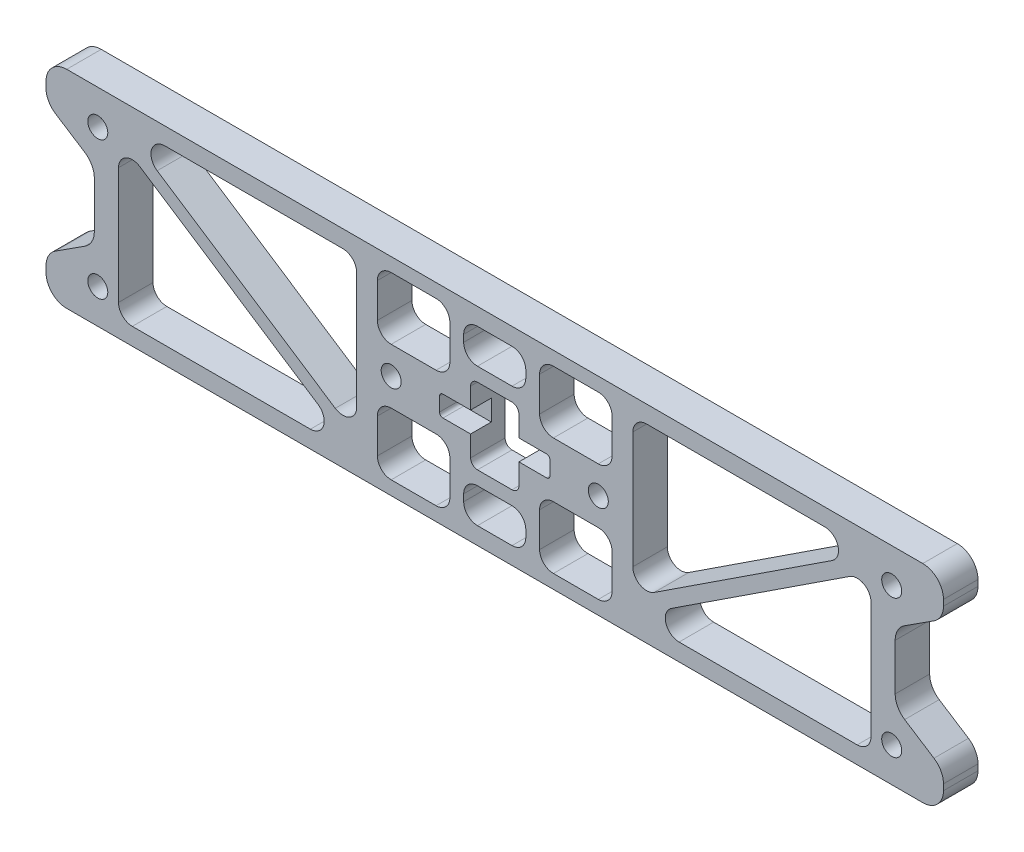
SolidWorks part; units mm, degrees
material "Thornel Mat VMA"
ref_plane "前视基准面" through (0, 0, 0) normal (0, 0, 1) x (1, 0, 0)
ref_plane "上视基准面" through (0, 0, 0) normal (0, 1, 0) x (1, 0, 0)
ref_plane "右视基准面" through (0, 0, 0) normal (1, 0, 0) x (0, 0, -1)
sketch "草图1" plane through (0, 0, 0) normal (0, 0, 1) x (1, 0, 0)
  line L0 (-57.5, 15) -> (-57.5, -15) construction
  line L1 (-65, -15) -> (65, -15)
  line L2 (-65, -15) -> (-65, 15)
  line L3 (-65, 15) -> (65, 15)
  line L4 (65, -15) -> (65, 15)
  line L5 (-65, -15) -> (65, 15) construction
  line L6 (-65, 15) -> (65, -15) construction
  line L7 (57.5, -15) -> (57.5, 15) construction
  line L8 (0, -1000) -> (0, 49000) construction
  line L9 (15, 0) -> (-15, 0) construction
  circle A0 centre (-57.5, -10) radius 1.45
  circle A1 centre (-57.5, 10) radius 1.45
  circle A2 centre (57.5, -10) radius 1.45
  circle A3 centre (57.5, 10) radius 1.45
  circle A4 centre (-15, 0) radius 1.45
  circle A5 centre (15, 0) radius 1.45
  point P0 (0, 0)
  point P23 (0, 0)
  dimension "D5" = 2.9
  dimension "D6" = 20
  dimension "D7" = 5
  dimension "D8" = 2.9
  dimension "D1" = 130
  dimension "D2" = 7.5
  dimension "D3" = 7.5
  dimension "D4" = 30
  dimension "D9" = 30
extrude "凸台-拉伸1" add sketch "草图1" along normal blind 5
sketch "草图3" plane through (0, 0, 5) normal (0, 0, 1) x (1, 0, 0)
  line L1 (-8, -1.5) -> (8, -1.5)
  line L2 (-8, -1.5) -> (-8, 1.5)
  line L3 (-8, 1.5) -> (8, 1.5)
  line L4 (8, -1.5) -> (8, 1.5)
  line L5 (-8, -1.5) -> (8, 1.5) construction
  line L6 (-8, 1.5) -> (8, -1.5) construction
  point P0 (0, 0)
  dimension "D1" = 3
  dimension "D2" = 16
extrude "切除-拉伸1" cut sketch "草图3" against normal blind 3
sketch "草图4" plane through (0, 0, 5) normal (0, 0, 1) x (1, 0, 0)
  line L1 (-3.5, -5.5) -> (3.5, -5.5)
  line L2 (-3.5, -5.5) -> (-3.5, 5.5)
  line L3 (-3.5, 5.5) -> (3.5, 5.5)
  line L4 (3.5, -5.5) -> (3.5, 5.5)
  line L5 (-3.5, -5.5) -> (3.5, 5.5) construction
  line L6 (-3.5, 5.5) -> (3.5, -5.5) construction
  point P0 (0, 0)
  dimension "D1" = 7
  dimension "D2" = 11
extrude "切除-拉伸2" cut sketch "草图4" against normal through all
sketch "草图6" plane through (0, 0, 5) normal (0, 0, 1) x (1, 0, 0)
  line L0 (-65, 9.5) -> (-58, 5)
  line L1 (-65, 15) -> (-65, -15) construction
  line L2 (-58, 5) -> (-58, -5)
  line L3 (-58, -5) -> (-65, -9.5)
  line L4 (-65, -9.5) -> (-65, 9.5)
  line L5 (-54.5, 12.5) -> (-54.5, -12.5)
  line L6 (-54.5, -12.5) -> (-20, -12.5)
  line L7 (-20, -12.5) -> (-20, 12.5)
  line L8 (-20, 12.5) -> (-54.5, 12.5)
  line L9 (-17, 13) -> (-17, 4)
  line L10 (-17, 4) -> (-6.5, 4)
  line L11 (-6.5, 4) -> (-6.5, 13)
  line L12 (-6.5, 13) -> (-17, 13)
  line L13 (65, 15) -> (-65, 15) construction
  line L14 (-65, -15) -> (65, -15) construction
  line L15 (-3.5, 5.5) -> (-3.5, 1.5) construction
  line L16 (0, -1000) -> (0, 49000) construction
  line L17 (-1000, 0) -> (49000, 0) construction
  line L18 (-6.5, -4) -> (-6.5, -13)
  line L19 (-17, -4) -> (-6.5, -4)
  line L20 (-17, -13) -> (-17, -4)
  line L21 (-6.5, -13) -> (-17, -13)
  line L22 (6.5, -13) -> (17, -13)
  line L23 (17, -13) -> (17, -4)
  line L24 (17, -4) -> (6.5, -4)
  line L25 (6.5, -4) -> (6.5, -13)
  line L26 (6.5, 13) -> (17, 13)
  line L27 (6.5, 4) -> (6.5, 13)
  line L28 (17, 4) -> (6.5, 4)
  line L29 (17, 13) -> (17, 4)
  line L30 (20, 12.5) -> (54.5, 12.5)
  line L31 (20, -12.5) -> (20, 12.5)
  line L32 (54.5, -12.5) -> (20, -12.5)
  line L33 (54.5, 12.5) -> (54.5, -12.5)
  line L34 (65, -9.5) -> (65, 9.5)
  line L35 (58, -5) -> (65, -9.5)
  line L36 (58, 5) -> (58, -5)
  line L37 (65, 9.5) -> (58, 5)
  line L38 (3.5, 5.5) -> (-3.5, 5.5) construction
  line L39 (-4.5, 12.5) -> (4.5, 12.5)
  line L40 (-4.5, 12.5) -> (-4.5, 7.5)
  line L41 (-4.5, 7.5) -> (4.5, 7.5)
  line L42 (4.5, 12.5) -> (4.5, 7.5)
  line L43 (-4.5, -7.5) -> (4.5, -7.5)
  line L44 (4.5, -12.5) -> (4.5, -7.5)
  line L45 (-4.5, -12.5) -> (4.5, -12.5)
  line L46 (-4.5, -12.5) -> (-4.5, -7.5)
  circle A0 centre (-57.5, 10) radius 1.45 construction
  circle A1 centre (-57.5, -10) radius 1.45 construction
  circle A2 centre (-15, 0) radius 1.45 construction
  dimension "D1" = 0.5
  dimension "D2" = 5
  dimension "D3" = 0.5
  dimension "D4" = 5
  dimension "D5" = 7
  dimension "D6" = 3
  dimension "D7" = 2.5
  dimension "D8" = 2.5
  dimension "D9" = 5
  dimension "D10" = 2
  dimension "D11" = 3
  dimension "D12" = 4
  dimension "D13" = 3
  dimension "D14" = 2
  dimension "D15" = 2.5
  dimension "D16" = 2
  dimension "D17" = 2
extrude "切除-拉伸3" cut sketch "草图6" against normal through all
sketch "草图7" plane through (0, 0, 0) normal (0, 0, 1) x (1, 0, 0)
  line L0 (-54.5, 12.5) -> (-20, -10.1088)
  line L1 (-20, -12.5) -> (-20, 12.5) construction
  line L2 (-20, -10.1088) -> (-20, -12.5)
  line L3 (-20, -12.5) -> (-54.5, 10.1088)
  line L4 (-54.5, 12.5) -> (-54.5, -12.5) construction
  line L5 (-54.5, 10.1088) -> (-54.5, 12.5)
  line L6 (54.5, 12.5) -> (54.5, 10.1088)
  line L7 (54.5, -12.5) -> (54.5, 12.5) construction
  line L8 (54.5, 10.1088) -> (20, -12.5)
  line L9 (20, -12.5) -> (20, -10.1088)
  line L10 (20, 12.5) -> (20, -12.5) construction
  line L11 (20, -10.1088) -> (54.5, 12.5)
  dimension "D1" = 2
  dimension "D2" = 2
extrude "凸台-拉伸2" add sketch "草图7" along normal up to surface (5 mm away) up to face at (0, -10, 5)
fillet "圆角1" radius 2 36 edges at (54.5, 10.1088, 2.5) (20, -12.5, 2.5) (54.5, -12.5, 2.5) (54.5, 12.5, 2.5) (20, -10.1088, 2.5) (20, 12.5, 2.5) (17, -4, 2.5) (17, -13, 2.5) (6.5, -13, 2.5) (6.5, -4, 2.5) (17, 13, 2.5) (17, 4, 2.5) (6.5, 4, 2.5) (6.5, 13, 2.5) (-6.5, -4, 2.5) (-6.5, -13, 2.5) (-17, -13, 2.5) (-17, -4, 2.5) (-6.5, 13, 2.5) (-6.5, 4, 2.5) (-17, 4, 2.5) (-17, 13, 2.5) (-54.5, 12.5, 2.5) (-20, -10.1088, 2.5) (-20, 12.5, 2.5) (-54.5, 10.1088, 2.5) (-20, -12.5, 2.5) (-54.5, -12.5, 2.5) (4.5, -7.5, 2.5) (4.5, -12.5, 2.5) (-4.5, -12.5, 2.5) (-4.5, -7.5, 2.5) (4.5, 12.5, 2.5) (4.5, 7.5, 2.5) (-4.5, 7.5, 2.5) (-4.5, 12.5, 2.5)
fillet "圆角2" radius 3 12 edges at (65, 15, 2.5) (65, 9.5, 2.5) (58, 5, 2.5) (58, -5, 2.5) (65, -9.5, 2.5) (65, -15, 2.5) (-65, -15, 2.5) (-65, -9.5, 2.5) (-58, -5, 2.5) (-58, 5, 2.5) (-65, 9.5, 2.5) (-65, 15, 2.5)
fillet "圆角3" radius 1 4 edges at (3.5, -5.5, 2.5) (-3.5, -5.5, 2.5) (-3.5, 5.5, 2.5) (3.5, 5.5, 2.5)
fillet "圆角4" radius 0.5 4 edges at (8, -1.5, 3.5) (-8, 1.5, 3.5) (-8, -1.5, 3.5) (8, 1.5, 3.5)
